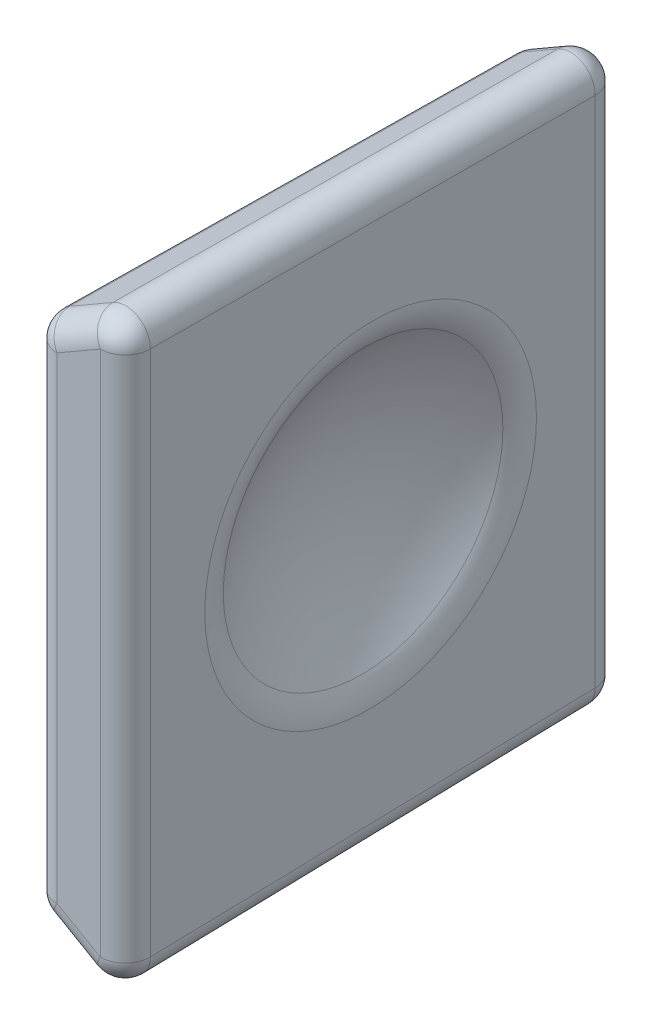
SolidWorks part; units mm, degrees
ref_plane "Front Plane" through (0, 0, 0) normal (0, 0, 1) x (1, 0, 0)
ref_plane "Top Plane" through (0, 0, 0) normal (0, 1, 0) x (1, 0, 0)
ref_plane "Right Plane" through (0, 0, 0) normal (1, 0, 0) x (0, 0, -1)
sketch "Sketch1" plane through (0, 0, 0) normal (0, 0, 1) x (1, 0, 0)
  line L0 (-3.7501, 10.4329) -> (-3.7501, -10.4329)
  line L1 (-3.7501, 10.4329) -> (0, 12.5981) construction
  line L2 (0, 12.5981) -> (0, -12.5981)
  line L3 (-3.7501, 9.8556) -> (0.25, 12.1651)
  line L4 (-3.5001, 9.9999) -> (0.25, 12.1651) construction
  line L6 (-4.5, 13.6931) -> (-4.5, 10.8659) construction
  line L7 (-5.1158, 9.6445) -> (0.5057, 12.8901) construction
  line L8 (2, 13.6931) -> (-4.5, 13.6931) construction
  line L12 (0.5057, -12.8901) -> (-5.1158, -9.6445) construction
  line L13 (-4.5, -10.8659) -> (-4.5, -13.6931) construction
  line L14 (-4.5, -13.6931) -> (2, -13.6931) construction
  line L15 (0, -12.5981) -> (-3.7501, -10.4329)
  line L42 (-10, 16.25) -> (-10, 6.5) construction
  line L43 (-10, 6.5) -> (-1.5, 6.5) construction
  line L44 (-0.5, 5.5) -> (-0.5, -5.5) construction
  line L45 (-1.5, -6.5) -> (-10, -6.5) construction
  line L46 (-10, -6.5) -> (-10, -16.25) construction
  line L47 (-10, -16.25) -> (-5.3404, -16.25) construction
  line L48 (-5.3404, -16.25) -> (-5.3404, -10.2761) construction
  line L49 (-3.8407, -9.4102) -> (0, -11.6276) construction
  line L50 (0, -12.5981) -> (0, -3.3912) construction
  line L51 (0, -3.3912) -> (0, 0) construction
  line L52 (0, 0) -> (0, 3.3912) construction
  line L53 (0, 3.3912) -> (0, 12.5981) construction
  line L54 (0, 11.6276) -> (-3.8407, 9.4102) construction
  line L55 (-5.3404, 10.2761) -> (-5.3404, 16.25) construction
  line L56 (-5.3404, 16.25) -> (-10, 16.25) construction
  arc A4 (-0.5, 5.5) -> (-1.5, 6.5) centre (-1.5, 5.5) ccw construction
  arc A5 (-1.5, -6.5) -> (-0.5, -5.5) centre (-1.5, -5.5) ccw construction
  ellipse E2 centre (-3.9999, 10.8662) end of major axis (-3.7498, 11.2994) minor radius 0.5 (-4.5, 10.8659) -> (-3.7501, 10.4329) ccw construction
  ellipse E4 centre (-3.9999, -10.8662) end of major axis (-3.7498, -11.2994) minor radius 0.5 (-3.7501, -10.4329) -> (-4.5, -10.8659) ccw construction
  ellipse E8 centre (-4.3403, -10.2766) end of major axis (-3.84, -11.1432) minor radius 1 (-3.8407, -9.4102) -> (-5.3404, -10.2761) ccw construction
  ellipse E9 centre (-4.3403, 10.2766) end of major axis (-4.8406, 9.4101) minor radius 1 (-5.3404, 10.2761) -> (-3.8407, 9.4102) ccw construction
  spline S2 degree 3 poles (0.5057, 12.8901) (0.5934, 13.0091) (0.6911, 13.1179) (0.9084, 13.3134) (1.0296, 13.4008) (1.2849, 13.5423) (1.4197, 13.5975) (1.7049, 13.6735) (1.8518, 13.6931) (2, 13.6931) knots 0 0 0 0 0.25 0.25 0.5 0.5 0.75 0.75 1 1 1 1 construction
  spline S4 degree 3 poles (2, -13.6931) (1.8519, -13.6931) (1.7072, -13.6738) (1.4242, -13.599) (1.2859, -13.5428) (1.0303, -13.4013) (0.9097, -13.3145) (0.6912, -13.1181) (0.5933, -13.0091) (0.5057, -12.8901) knots 0 0 0 0 0.25 0.25 0.5 0.5 0.75 0.75 1 1 1 1 construction
  dimension "D1" = 0.5
extrude "Boss-Extrude1" add sketch "Sketch1" against normal blind 20 draft 0.5 contours L15 L2 L3 L0
fillet "Fillet1" radius 1 12 edges at (-0.0873, -12.4469, -10) (-3.6628, -10.3826, -10) (-3.6628, 9.8052, -10) (-0.0873, 11.8696, -10) (-3.5756, -0.2887, -20) (-1.8751, 10.7366, -20) (-0.1745, -0.2887, -20) (-1.8751, -11.314, -20) (-3.7501, -0.2887, 0) (-1.8751, 10.9382, 0) (0, -0.2887, 0) (-1.8751, -11.5155, 0)
sketch "Sketch2" plane through (0, 0, 0) normal (0, 1, 0) x (1, 0, 0)
  line L0 (0, 0) -> (0, 10.0007)
  line L1 (0, 10.0007) -> (8.7268, 10.0007)
  line L2 (8.7268, 20.7276) -> (8.7268, -0.7261)
  line L3 (-0.6702, 20) -> (-0.1702, 20)
  line L4 (-0.1702, 20) -> (0, 10.0007)
  circle A0 centre (8.7268, 10.0007) radius 10.7268
  arc A1 (-0.1702, 19.5044) -> (-0.6702, 20) centre (-0.6702, 19.5) ccw construction
  arc A2 (-0.1702, 19.5044) -> (-0.6702, 20) centre (-0.6702, 19.5) ccw construction
  point P5 (-2, 10.0007)
  dimension "D1" = 2
revolve "Cut-Revolve1" cut sketch "Sketch2" angle 360 about L2
fillet "Fillet2" radius 2 1 edges at (-0.14, 0, -16.0377)
